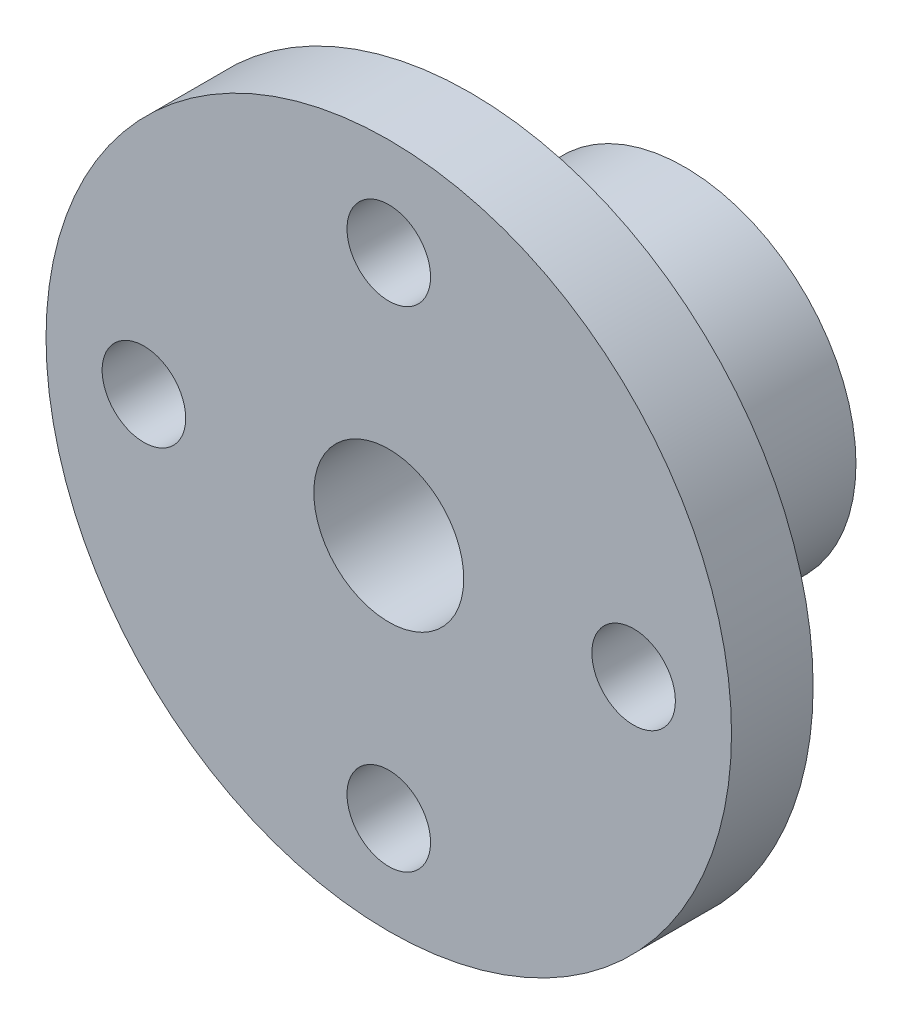
SolidWorks part; units mm, degrees
ref_plane "Front Plane" through (0, 0, 0) normal (0, 0, 1) x (1, 0, 0)
ref_plane "Top Plane" through (0, 0, 0) normal (0, 1, 0) x (1, 0, 0)
ref_plane "Right Plane" through (0, 0, 0) normal (1, 0, 0) x (0, 0, -1)
sketch "Sketch1" plane through (0, 0, 0) normal (0, 0, 1) x (1, 0, 0)
  circle A0 centre (0, 0) radius 3.5
  circle A1 centre (0, 0) radius 8
  dimension "D1" = 7
  dimension "D2" = 16
extrude "Boss-Extrude1" add sketch "Sketch1" along normal blind 10
sketch "Sketch2" plane through (0, 0, 10) normal (0, 0, 1) x (1, 0, 0)
  circle A0 centre (0, 0) radius 3.5
  circle A1 centre (0, 0) radius 16
  circle A2 centre (0, 0) radius 3.5 construction
  dimension "D1" = 32
extrude "Boss-Extrude2" add sketch "Sketch2" along normal blind 3.81
sketch "Sketch3" plane through (0, 0, 13.81) normal (0, 0, 1) x (1, 0, 0)
  circle A0 centre (0, 11.43) radius 1.95
  circle A1 centre (11.43, 0) radius 1.95
  circle A2 centre (0, -11.43) radius 1.95
  circle A3 centre (-11.43, 0) radius 1.95
  point P12 (0, 0)
  dimension "D1" = 3.9
  dimension "D2" = 11.43
  dimension "D3" = 4
extrude "Cut-Extrude1" cut sketch "Sketch3" against normal through all
sketch "Sketch4" plane through (0, 0, 0) normal (0, 1, 0) x (1, 0, 0)
  line L0 (8, 0) -> (-8, 0) construction
  circle A0 centre (0, -5) radius 2
  dimension "D1" = 4
  dimension "D2" = 5
extrude "Cut-Extrude2" cut sketch "Sketch4" against normal through all
